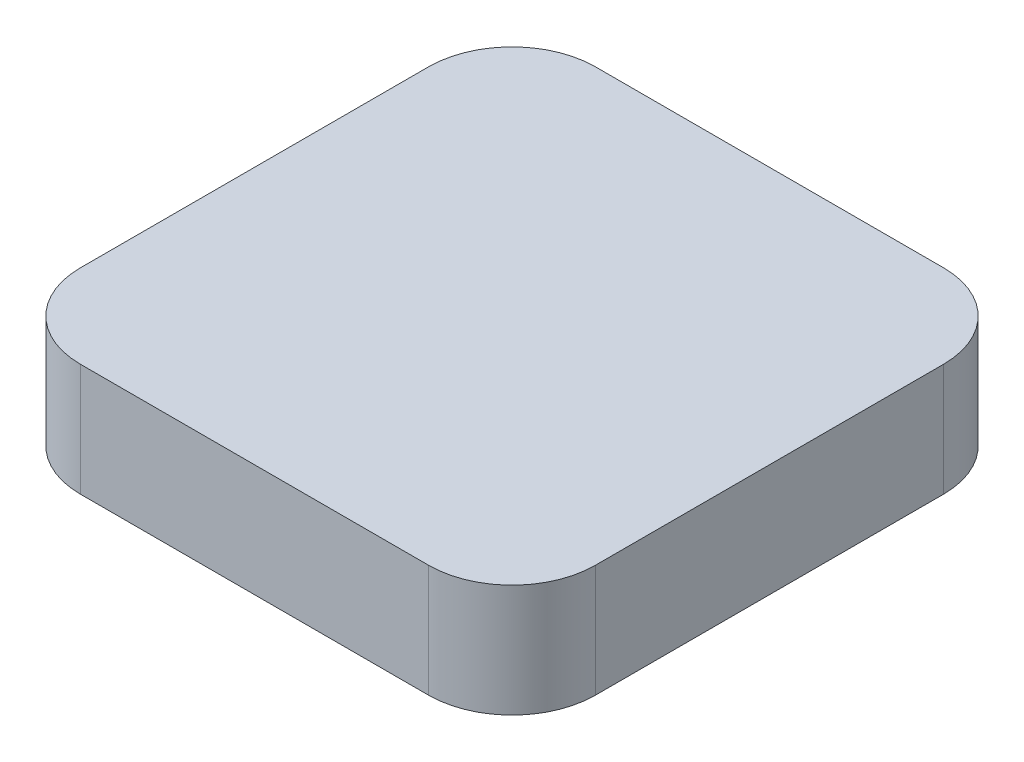
SolidWorks part; units mm, degrees
ref_plane "Front Plane" through (0, 0, 0) normal (0, 0, 1) x (1, 0, 0)
ref_plane "Top Plane" through (0, 0, 0) normal (0, 1, 0) x (1, 0, 0)
ref_plane "Right Plane" through (0, 0, 0) normal (1, 0, 0) x (0, 0, -1)
sketch "Sketch1" plane through (0, 0, 0) normal (0, 1, 0) x (1, 0, 0)
  line L1 (-49, -49) -> (49, -49)
  line L2 (-49, -49) -> (-49, 49)
  line L3 (-49, 49) -> (49, 49)
  line L4 (49, -49) -> (49, 49)
  line L5 (-49, -49) -> (49, 49) construction
  line L6 (-49, 49) -> (49, -49) construction
  point P0 (0, 0)
  dimension "D1" = 98
extrude "Boss-Extrude1" add sketch "Sketch1" along normal blind 23
fillet "Fillet1" radius 15.875 4 edges at (-49, 11.5, -49) (-49, 11.5, 49) (49, 11.5, -49) (49, 11.5, 49)
sketch "Sketch2" plane through (0, 0, 0) normal (0, -1, 0) x (1, 0, 0)
  circle A0 centre (0, 0) radius 38.1
  dimension "D1" = 76.2
sketch "Sketch3" plane through (0, 0, 0) normal (0, 0, 1) x (1, 0, 0)
  line L0 (-63.5, 0) -> (-63.5, 1.5875)
  line L1 (-49, 0) -> (-33.125, 0) construction
  line L2 (-38.1, 0) -> (-63.5, 0)
  line L3 (-63.5, 1.5875) -> (-49, 1.5875)
  line L4 (-49, 0) -> (-49, 23) construction
  arc A0 (-49, 1.5875) -> (-38.1, 0) centre (-49, -36.6267) cw
  dimension "D1" = 1.5875
  dimension "D3" = 25.4
sweep "Cut-Sweep3" cut profiles "Sketch3" path "Sketch2"
sketch "Sketch4" plane through (0, 0, -49) normal (0, 0, -1) x (-1, 0, 0)
  line L0 (-29.188, 7.69) -> (-26.648, 7.69)
  line L1 (-26.648, 7.69) -> (-25.9764, 9.3019)
  line L2 (-24.1446, 9.3019) -> (-23.473, 7.69)
  line L3 (-23.473, 7.69) -> (-20.933, 7.69)
  line L4 (-20.933, 15.31) -> (-23.473, 15.31)
  line L5 (-23.473, 15.31) -> (-24.1446, 13.6981)
  line L6 (-25.9764, 13.6981) -> (-26.648, 15.31)
  line L7 (-26.648, 15.31) -> (-29.188, 15.31)
  line L9 (0, 0) -> (0, 23) construction
  line L10 (-33.125, 23) -> (33.125, 23) construction
  line L11 (-15.875, 16.707) -> (-3.175, 16.707)
  line L12 (-20.933, 11.5) -> (0, 11.5) construction
  line L13 (-3.175, 16.707) -> (-3.175, 15.1195)
  line L14 (-3.175, 15.1195) -> (-4.7625, 13.532)
  line L15 (-4.7625, 13.532) -> (-14.2875, 13.532)
  line L16 (-14.2875, 13.532) -> (-15.875, 15.1195)
  line L17 (-15.875, 15.1195) -> (-15.875, 16.707)
  line L18 (7.598, 18.6438) -> (7.598, 23) construction
  line L19 (1.248, 5.9437) -> (13.948, 5.9437)
  line L20 (1.248, 5.9437) -> (1.248, 18.6438)
  line L21 (1.248, 18.6438) -> (13.948, 18.6438)
  line L22 (13.948, 5.9437) -> (13.948, 18.6438)
  line L23 (1.248, 5.9437) -> (13.948, 18.6438) construction
  line L24 (1.248, 18.6438) -> (13.948, 5.9437) construction
  line L25 (17.123, 5.9437) -> (32.998, 5.9437)
  line L26 (17.123, 5.9437) -> (17.123, 18.6438)
  line L27 (17.123, 18.6438) -> (32.998, 18.6438)
  line L28 (32.998, 5.9437) -> (32.998, 18.6438)
  line L29 (17.123, 5.9437) -> (32.998, 18.6438) construction
  line L30 (17.123, 18.6438) -> (32.998, 5.9437) construction
  line L31 (7.598, 5.9437) -> (7.598, 1.5875) construction
  line L33 (0, 1.5875) -> (49, 1.5875) construction
  line L35 (-33.125, 23) -> (-33.125, 1.5875) construction
  line L36 (33.125, 1.5875) -> (33.125, 23) construction
  arc A0 (-25.9764, 9.3019) -> (-24.1446, 9.3019) centre (-25.0605, 8.9203) cw
  arc A1 (-20.933, 7.69) -> (-20.933, 15.31) centre (-20.933, 11.5) ccw
  arc A2 (-24.1446, 13.6981) -> (-25.9764, 13.6981) centre (-25.0605, 14.0797) cw
  arc A3 (-29.188, 15.31) -> (-29.188, 7.69) centre (-29.188, 11.5) ccw
  point P26 (7.598, 12.2937)
  point P35 (25.0605, 12.2937)
  dimension "D2" = 3.175
  dimension "D3" = 15.875
  dimension "D1" = 7.62
  dimension "D4" = 2.54
  dimension "D5" = 3.175
  dimension "D6" = 12.7
  dimension "D7" = 135
  dimension "D8" = 1.5875
  dimension "D9" = 12.7
  dimension "D10" = 2.032
  dimension "D11" = 0.127
  dimension "D12" = 3.175
  dimension "D13" = 15.875
  dimension "D14" = 3.175
  dimension "D15" = 0.127
extrude "Cut-Extrude1" cut sketch "Sketch4" against normal blind 12.7
